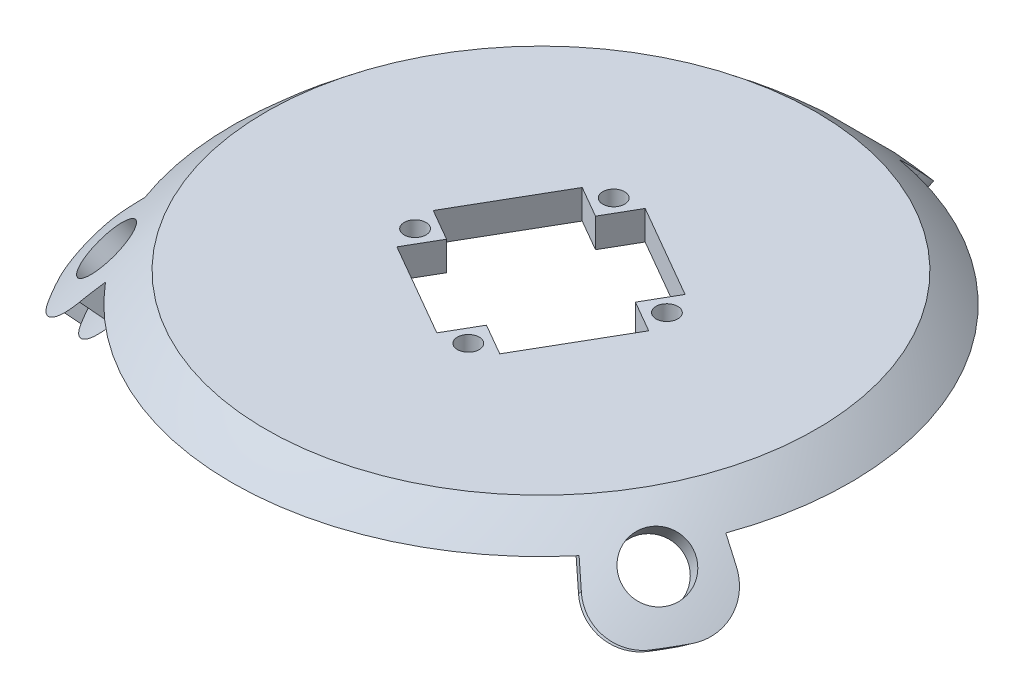
SolidWorks part; units mm, degrees
ref_plane "前视基准面" through (0, 0, 0) normal (0, 0, 1) x (1, 0, 0)
ref_plane "上视基准面" through (0, 0, 0) normal (0, 1, 0) x (1, 0, 0)
ref_plane "右视基准面" through (0, 0, 0) normal (1, 0, 0) x (0, 0, -1)
sketch "草图1" plane through (0, 0, 0) normal (0, 0, 1) x (1, 0, 0)
  line L0 (0, 0) -> (0, 62) construction
  line L1 (0, 0) -> (43.8406, 43.8406) construction
  line L2 (0, 0) -> (49.1173, 37.835) construction
  line L3 (0, 0) -> (37.835, 49.1173) construction
  line L4 (37.835, 49.1173) -> (0, 49.1173)
  line L5 (0, 49.1173) -> (0, 45.1173)
  line L6 (0, 45.1173) -> (36.4476, 45.1173)
  line L7 (49.1173, 37.835) -> (45.9485, 35.394)
  arc A0 (49.1173, 37.835) -> (37.835, 49.1173) centre (0, 0) ccw
  arc A1 (45.9485, 35.394) -> (36.4476, 45.1173) centre (0, 0) ccw
  dimension "D1" = 45
  dimension "D4" = 58
  dimension "D5" = 62
  dimension "D2" = 7.393
  dimension "D3" = 7.393
  dimension "D6" = 4
revolve "旋转1" add sketch "草图1" angle 360 about L0
ref_plane "基准面1" through (0, 0, 0) normal (0, -0.7071, 0.7071) x (1, 0, 0)
sketch "草图2" plane through (0, 0, 0) normal (0, -0.7071, 0.7071) x (1, 0, 0)
  circle A0 centre (0, 0) radius 4
extrude "切除-拉伸1" cut sketch "草图2" against normal through all
pattern_circular "阵列(圆周)1" count 3 over 360 about axis through (0, 49.1173, 0) along (0, -1, 0) of "切除-拉伸1"
sketch "草图5" plane through (0, 45.1173, 0) normal (0, -1, 0) x (1, 0, 0)
  line L0 (0, 0) -> (86.6025, 50) construction
  line L1 (0, 0) -> (61.2522, 51.3967) construction
  line L2 (0, 0) -> (0, 53.6433) construction
  line L3 (0, 0) -> (41.0931, 34.4812)
  line L4 (0, 0) -> (50.4082, 18.3471)
  line L5 (0, 0) -> (-9.3151, -52.8283)
  line L6 (0, 0) -> (9.3151, -52.8283)
  line L7 (0, 0) -> (-41.0931, 34.4812)
  line L8 (0, 0) -> (-50.4082, 18.3471)
  arc A0 (9.3151, -52.8283) -> (50.4082, 18.3471) centre (0, 0) ccw
  arc A1 (-50.4082, 18.3471) -> (-9.3151, -52.8283) centre (0, 0) ccw
  arc A2 (41.0931, 34.4812) -> (-41.0931, 34.4812) centre (0, 0) ccw
  point P14 (0, 0)
  dimension "D1" = 10
  dimension "D2" = 60
  dimension "D3" = 3
extrude "切除-拉伸2" cut sketch "草图5" along normal through all contours L6 A0 L4 | L3 A2 L7 | L8 A1 L5
fillet "圆角1" radius 6 6 edges at (44.6663, 36.6145, 16.2572) (36.4123, 36.6145, 30.5536) (-44.6663, 36.6145, 16.2572) (-36.4123, 36.6145, 30.5536) (-8.254, 36.6145, -46.8108) (8.254, 36.6145, -46.8108)
sketch "草图6" plane through (0, 49.1173, 0) normal (0, 1, 0) x (1, 0, 0)
  line L0 (0, 0) -> (-37.835, 0) construction
  line L1 (0, 0) -> (-18.9175, -32.7661) construction
  line L2 (14.5753, 0.2452) -> (7.0753, -12.7452)
  line L3 (12.7452, 7.0753) -> (-0.2452, 14.5753)
  line L4 (0.2452, -14.5753) -> (-12.7452, -7.0753)
  line L5 (-7.0753, 12.7452) -> (-14.5753, -0.2452)
  line L6 (17.0753, 4.5753) -> (-17.0753, -4.5753) construction
  line L7 (4.5753, -17.0753) -> (-4.5753, 17.0753) construction
  line L12 (-2.7452, 10.2452) -> (-7.0753, 12.7452)
  line L13 (-2.7452, 10.2452) -> (-0.2452, 14.5753)
  line L14 (10.2452, 2.7452) -> (12.7452, 7.0753)
  line L15 (10.2452, 2.7452) -> (14.5753, 0.2452)
  line L16 (2.7452, -10.2452) -> (7.0753, -12.7452)
  line L17 (2.7452, -10.2452) -> (0.2452, -14.5753)
  line L18 (-10.2452, -2.7452) -> (-12.7452, -7.0753)
  line L19 (-10.2452, -2.7452) -> (-14.5753, -0.2452)
  circle A0 centre (0, 0) radius 37.835 construction
  point P28 (0, 0)
  dimension "D1" = 60
  dimension "D2" = 15
  dimension "D3" = 45
  dimension "D4" = 25
  dimension "D6" = 4
extrude "切除-拉伸3" cut sketch "草图6" against normal through all contours L3 L13 L12 L5 L19 L18 L4 L17 L16 L2 L15 L14
sketch "草图7" plane through (0, 49.1173, 0) normal (0, 1, 0) x (1, 0, 0)
  line L0 (2.7452, -10.2452) -> (7.0753, -12.7452) construction
  line L2 (2.7452, -10.2452) -> (0.2452, -14.5753) construction
  circle A0 centre (3.6603, -13.6603) radius 1.5
  point P4 (0, 0)
  point P6 (1.146, -13.015)
  dimension "D1" = 2.5
  dimension "D2" = 2.5
extrude "切除-拉伸4" cut sketch "草图7" against normal blind 10
pattern_circular "阵列(圆周)2" count 4 over 360 about axis through (0, 0, 0) along (0, 1, 0) of "切除-拉伸4"
